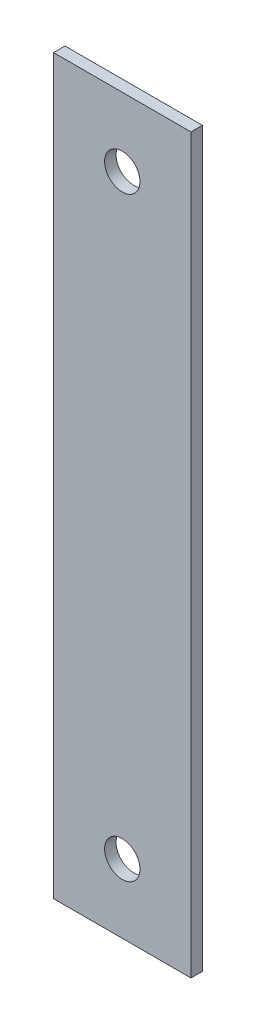
SolidWorks part; units mm, degrees
material "Plain Carbon Steel"
ref_plane "Front Plane" through (0, 0, 0) normal (0, 0, 1) x (1, 0, 0)
ref_plane "Top Plane" through (0, 0, 0) normal (0, 1, 0) x (1, 0, 0)
ref_plane "Right Plane" through (0, 0, 0) normal (1, 0, 0) x (0, 0, -1)
sketch "Sketch1" plane through (0, 0, 0) normal (0, 0, 1) x (1, 0, 0)
  line L1 (0, 0) -> (38.1, 0)
  line L2 (0, 0) -> (0, 203.2)
  line L3 (0, 203.2) -> (38.1, 203.2)
  line L4 (38.1, 0) -> (38.1, 203.2)
  dimension "D1" = 38.1
  dimension "D2" = 203.2
extrude "Boss-Extrude1" add sketch "Sketch1" along normal blind 3.175
hole_wizard "W (0.386) Diameter Hole1" positions "Sketch3" profile "Sketch2" hole size "W" standard "ANSI Inch" end condition through all
sketch "Sketch3" plane through (0, 0, 3.175) normal (0, 0, 1) x (1, 0, 0)
  line L0 (19.05, 0) -> (19.05, 19.05) construction
  line L1 (0, 0) -> (38.1, 0) construction
  line L2 (19.05, 19.05) -> (19.05, 184.15) construction
  line L3 (19.05, 184.15) -> (19.05, 203.2) construction
  line L4 (38.1, 203.2) -> (0, 203.2) construction
  point P0 (19.05, 184.15)
  point P2 (19.05, 19.05)
  dimension "D1" = 19.05
sketch "Sketch2" plane through (19.05, 184.15, 3.175) normal (1, 0, 0) x (0, -1, 0)
  line L0 (0, 0) -> (0, 3.175)
  line L1 (0, 3.175) -> (4.9022, 3.175)
  line L2 (4.9022, 3.175) -> (4.9022, 0)
  line L5 (4.9022, 0) -> (0, 0)
  line L11 (0, -6.35) -> (0, 107.95) construction
  dimension "Thru Hole Dia." = 9.8044
  dimension "Thru Hole Depth" = 3.175
